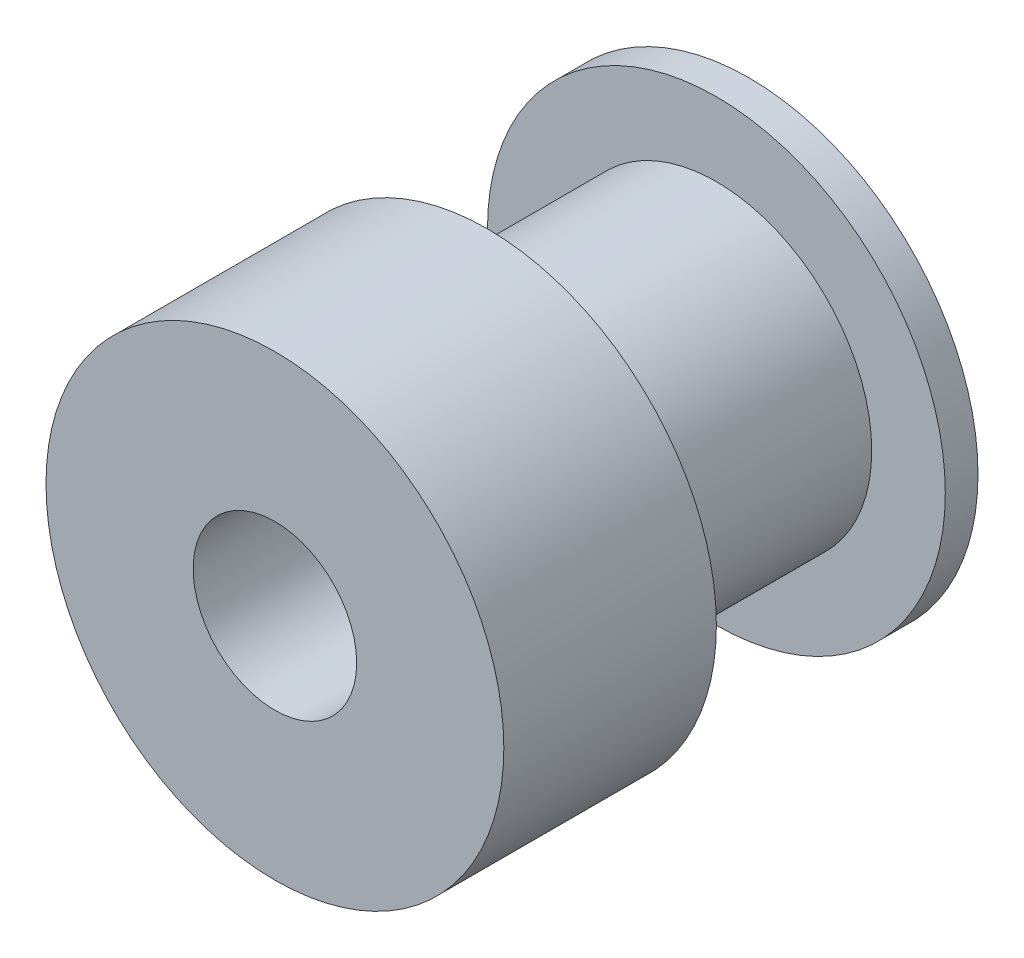
SolidWorks part; units mm, degrees
ref_plane "前视基准面" through (0, 0, 0) normal (0, 0, 1) x (1, 0, 0)
ref_plane "上视基准面" through (0, 0, 0) normal (0, 1, 0) x (1, 0, 0)
ref_plane "右视基准面" through (0, 0, 0) normal (1, 0, 0) x (0, 0, -1)
sketch "草图1" plane through (0, 0, 0) normal (0, 0, 1) x (1, 0, 0)
  circle A0 centre (0, 0) radius 7
  dimension "D1" = 14
extrude "凸台-拉伸1" add sketch "草图1" along normal blind 1
sketch "草图2" plane through (0, 0, 1) normal (0, 0, 1) x (1, 0, 0)
  circle A0 centre (0, 0) radius 4.75
  dimension "D1" = 9.5
extrude "凸台-拉伸2" add sketch "草图2" along normal blind 7
sketch "草图3" plane through (0, 0, 8) normal (0, 0, 1) x (1, 0, 0)
  circle A0 centre (0, 0) radius 7
  dimension "D1" = 14
extrude "凸台-拉伸3" add sketch "草图3" along normal blind 6.5
sketch "草图4" plane through (0, 0, 14.5) normal (0, 0, 1) x (1, 0, 0)
  circle A0 centre (0, 0) radius 2.5
  dimension "D1" = 5
extrude "切除-拉伸1" cut sketch "草图4" against normal blind 16
